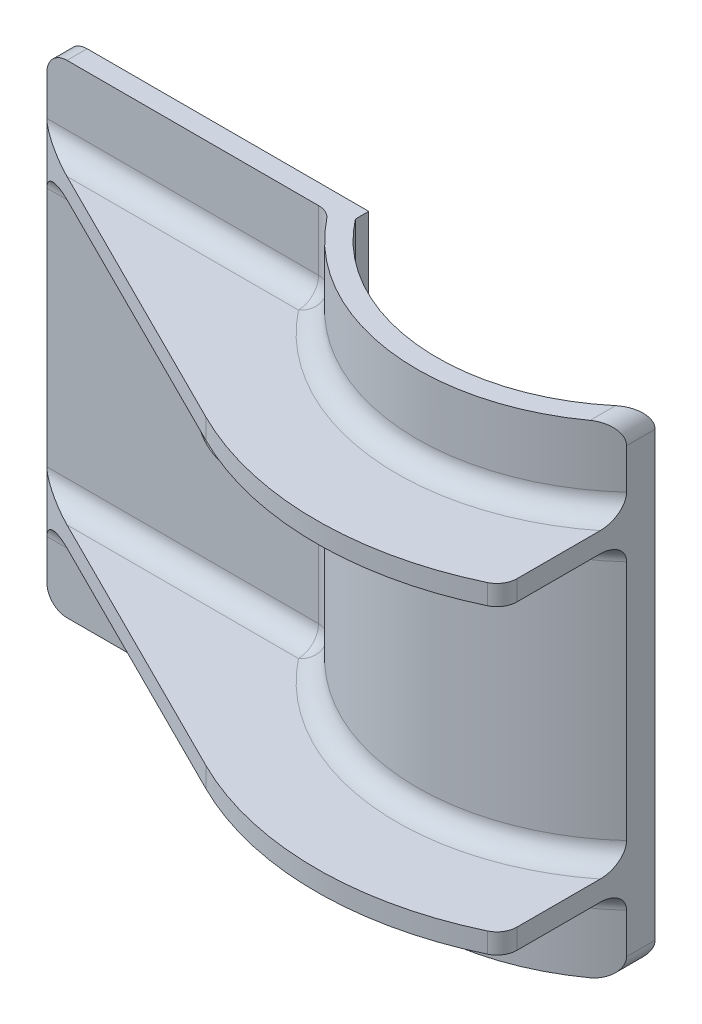
SolidWorks part; units mm, degrees
material "ABS"
ref_plane "Plan de face" through (0, 0, 0) normal (0, 0, 1) x (1, 0, 0)
ref_plane "Plan de dessus" through (0, 0, 0) normal (0, 1, 0) x (1, 0, 0)
ref_plane "Plan de droite" through (0, 0, 0) normal (1, 0, 0) x (0, 0, -1)
sketch "Esquisse1" plane through (0, 0, 0) normal (0, 1, 0) x (1, 0, 0)
  line L0 (7.5, -6.7646) -> (7.5, -8.1829)
  line L1 (-23, -5.5) -> (-8, -5.5)
  line L2 (-23, -5.5) -> (-23, -6.5)
  line L3 (-23, -6.5) -> (-8.9978, -6.5)
  line L4 (-8, -5.5) -> (-8, -6.1652)
  arc A0 (-8, -6.1652) -> (7.5, -6.7646) centre (0, 0) ccw
  arc A1 (7.5, -8.1829) -> (-8.9978, -6.5) centre (0, 0) cw
  dimension "D1" = 10.1
  dimension "D7" = 1
  dimension "D2" = 8
  dimension "D3" = 7.5
  dimension "D4" = 15
  dimension "D5" = 5.5
  dimension "D8" = 1
extrude "Boss.-Extru.1" add sketch "Esquisse1" along normal mid plane 24
sketch "Esquisse2" plane through (0, 12, 0) normal (0, 1, 0) x (1, 0, 0)
  line L0 (7.5, -8.1829) -> (7.5, -14.2464)
  line L1 (-7.2004, -14.4002) -> (-23, -6.5)
  line L2 (-23, -6.5) -> (-8.9978, -6.5) construction
  line L3 (-23, -6.5) -> (-8.9978, -6.5)
  arc A0 (7.5, -14.2464) -> (-7.2004, -14.4002) centre (0, 0) cw
  arc A1 (-8.9978, -6.5) -> (7.5, -8.1829) centre (0, 0) ccw construction
  arc A2 (-8.9978, -6.5) -> (7.5, -8.1829) centre (0, 0) ccw
  arc A3 (-8, -6.1652) -> (7.5, -6.7646) centre (0, 0) ccw construction
  dimension "D1" = 6
extrude "Boss.-Extru.2" add sketch "Esquisse2" against normal blind 1 from offset 4 offset against normal yes
mirror "Symétrie1" about plane through (0, 0, 0) normal (0, 1, 0) of "Boss.-Extru.2"
fillet "Congé1" radius 1 17 edges at (-8.9978, 10, 6.5) (-1.1264, 8, 11.0427) (-1.1264, 7, 11.0427) (-15.9989, 7, 6.5) (-15.9989, 8, 6.5) (-23, 12, 6) (7.5, 7.5, 14.2464) (7.5, 12, 7.4738) (-8.9978, -10, 6.5) (-8.9978, 0, 6.5) (-23, -12, 6) (7.5, -12, 7.4738) (7.5, -7.5, 14.2464) (-1.1264, -7, 11.0427) (-15.9989, -7, 6.5) (-1.1264, -8, 11.0427) (-15.9989, -8, 6.5)
sketch "Esquisse3" plane through (0, 0, 6.5) normal (0, 0, 1) x (1, 0, 0)
  line L0 (-8, 12) -> (-8, -12) construction
  circle A0 centre (-14, 0) radius 1.5
  dimension "D1" = 3
  dimension "D2" = 6
extrude "Enlèv. mat.-Extru.1" cut sketch "Esquisse3" against normal through all
